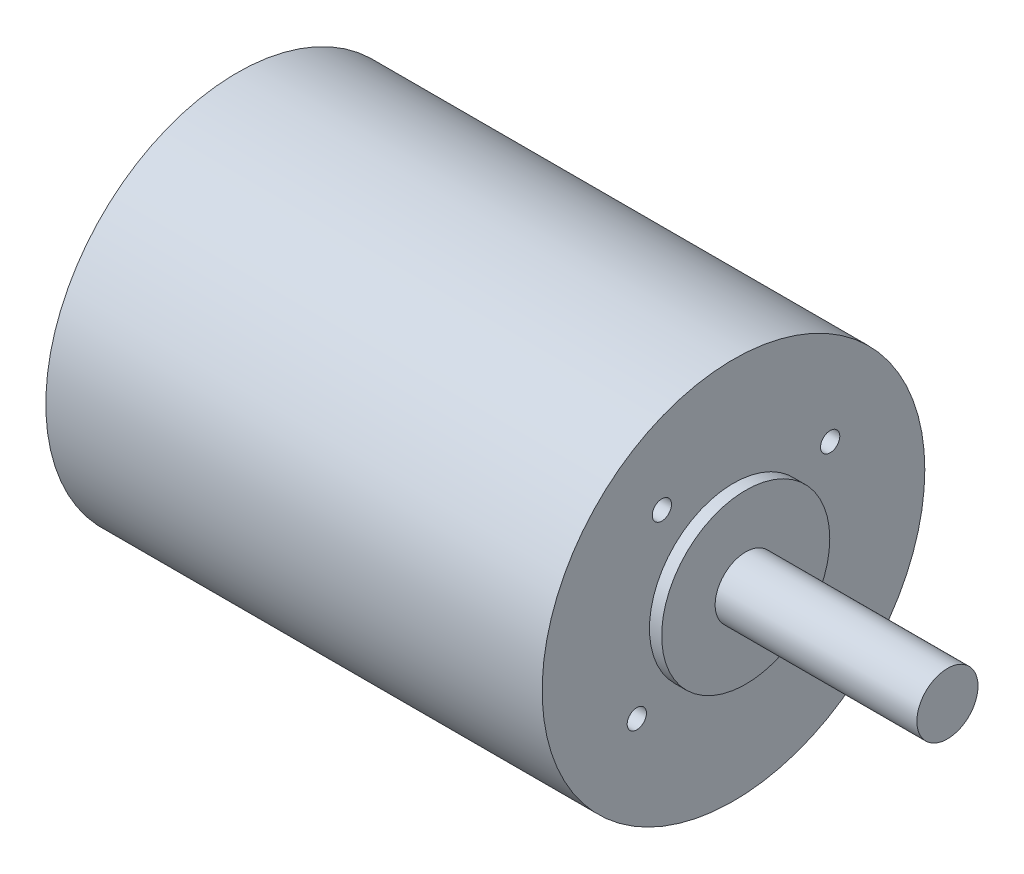
SolidWorks part; units mm, degrees
ref_plane "Front Plane" through (0, 0, 0) normal (0, 0, 1) x (1, 0, 0)
ref_plane "Top Plane" through (0, 0, 0) normal (0, 1, 0) x (1, 0, 0)
ref_plane "Right Plane" through (0, 0, 0) normal (1, 0, 0) x (0, 0, -1)
sketch "Sketch1" plane through (0, 0, 0) normal (1, 0, 0) x (0, 0, -1)
  circle A0 centre (0, 0) radius 39.751
  dimension "D1" = 79.502
extrude "Boss-Extrude1" add sketch "Sketch1" along normal blind 103.124
sketch "Sketch2" plane through (103.124, 0, 0) normal (1, 0, 0) x (0, 0, -1)
  circle A0 centre (0, 0) radius 17.4625
  dimension "D1" = 34.925
extrude "Boss-Extrude2" add sketch "Sketch2" along normal blind 2.54
sketch "Sketch3" plane through (105.664, 0, 0) normal (1, 0, 0) x (0, 0, -1)
  circle A0 centre (0, 0) radius 6.35
  dimension "D1" = 12.7
extrude "Boss-Extrude3" add sketch "Sketch3" along normal blind 41.91
sketch "Sketch4" plane through (0, 0, 0) normal (-1, 0, 0) x (0, 0, 1)
  circle A0 centre (0, 0) radius 6.35
  dimension "D1" = 12.7
extrude "Boss-Extrude4" add sketch "Sketch4" along normal blind 14.224
sketch "Sketch5" plane through (103.124, 0, 0) normal (1, 0, 0) x (0, 0, -1)
  line L0 (0, 0) -> (-14.8824, 20.086) construction
  circle A0 centre (-14.8824, 20.086) radius 2
  circle A1 centre (20.086, 14.8824) radius 2
  circle A2 centre (14.8824, -20.086) radius 2
  circle A3 centre (-20.086, -14.8824) radius 2
  point P14 (0, 0)
  dimension "D2" = 4
  dimension "D1" = 24.9987
  dimension "D3" = 4
extrude "Cut-Extrude1" cut sketch "Sketch5" against normal blind 6.858
equation "\"‪0.15748‬\"=0.216608"
